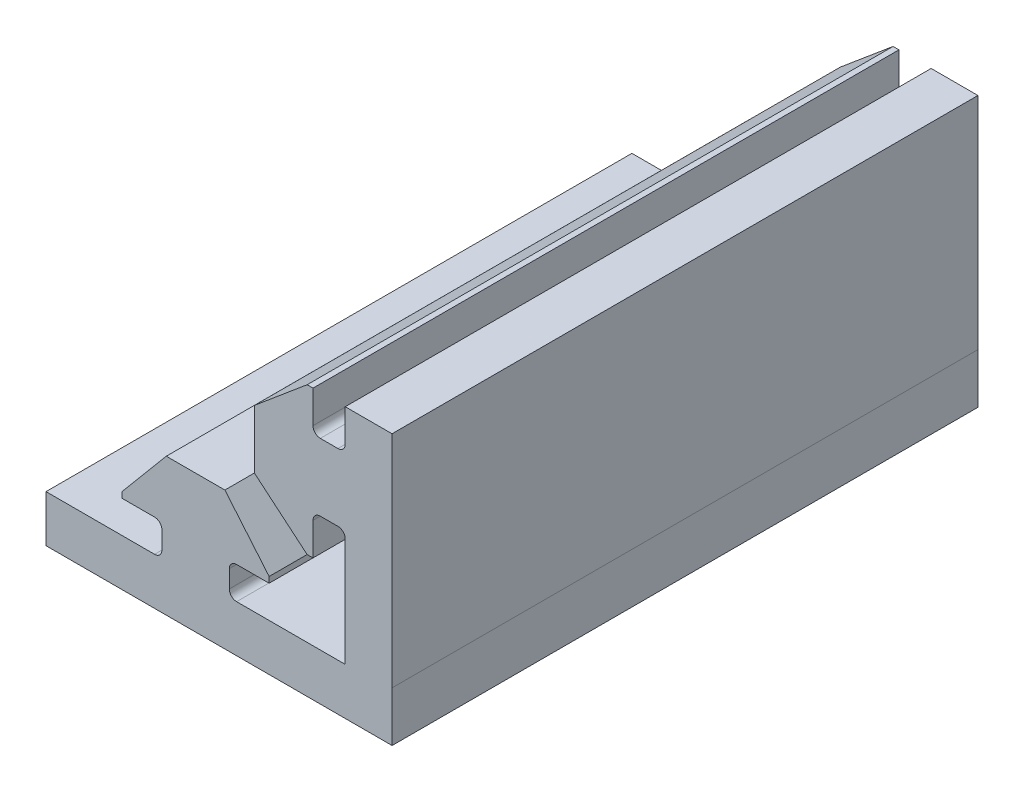
SolidWorks part; units mm, degrees
ref_plane "Front Plane" through (0, 0, 0) normal (0, 0, 1) x (1, 0, 0)
ref_plane "Top Plane" through (0, 0, 0) normal (0, 1, 0) x (1, 0, 0)
ref_plane "Right Plane" through (0, 0, 0) normal (1, 0, 0) x (0, 0, -1)
ref_plane "Plane1" through (0, 0, -3683) normal (0, 0, -1) x (-1, 0, 0)
sketch "Sketch1" plane through (0, 0, -3683) normal (0, 0, -1) x (-1, 0, 0)
  line L0 (7.9453, 3.5889) -> (-1.1987, 3.5889)
  line L1 (-1.8337, 4.2239) -> (-1.8337, 5.7479)
  line L2 (-1.1987, 6.3829) -> (1.6216, 6.3829)
  line L3 (1.6216, 6.3829) -> (1.6216, 6.8909)
  line L4 (1.6216, 6.8909) -> (-2.2147, 11.4629)
  line L5 (-2.2147, 11.4629) -> (-7.2947, 11.4629)
  line L6 (-7.2947, 11.4629) -> (-11.1311, 6.8909)
  line L7 (-11.1311, 6.8909) -> (-11.1311, 6.3829)
  line L8 (-11.1311, 6.3829) -> (-8.3107, 6.3829)
  line L9 (-7.6757, 5.7479) -> (-7.6757, 4.2239)
  line L10 (-8.3107, 3.5889) -> (-17.4547, 3.5889)
  line L11 (-17.7279, 3.8588) -> (-17.7284, 13.0024)
  line L12 (-17.4548, -0.4751) -> (7.9452, -0.4751)
  line L13 (-17.0929, 13.6378) -> (-15.5689, 13.6378)
  line L29 (-17.4547, 3.5889) -> (-17.7279, 3.5889)
  line L30 (-17.4548, -0.4751) -> (-17.7279, -0.4751)
  line L32 (8.2155, 3.5889) -> (8.2155, -0.4751)
  line L34 (8.2155, 3.5889) -> (7.9453, 3.5889)
  line L35 (8.2155, -0.4751) -> (7.9452, -0.4751)
  line L36 (-14.9339, 13.0028) -> (-14.9339, 10.1825)
  line L37 (-14.9339, 10.1825) -> (-14.4259, 10.1825)
  line L38 (-14.4259, 10.1825) -> (-9.8539, 14.0188)
  line L39 (-9.8539, 14.0188) -> (-9.8539, 19.0988)
  line L40 (-9.8539, 19.0988) -> (-14.4259, 22.9352)
  line L41 (-14.4259, 22.9352) -> (-14.9339, 22.9352)
  line L42 (-14.9339, 22.9352) -> (-14.9339, 20.1148)
  line L43 (-15.5689, 19.4798) -> (-17.0929, 19.4798)
  line L44 (-17.7287, 20.1156) -> (-17.7288, 22.9352)
  line L45 (-21.7872, 22.9352) -> (-21.7919, 3.8591)
  line L49 (-17.7288, 22.9352) -> (-21.7872, 22.9352)
  line L51 (-17.7279, 3.5889) -> (-17.7279, 3.8588)
  line L52 (-21.7919, 3.5889) -> (-21.7919, 3.8591)
  line L54 (-17.7279, -0.4751) -> (-21.7919, -0.4751)
  line L56 (-21.7919, -0.4751) -> (-21.7919, 3.5889)
  arc A0 (-1.1987, 3.5889) -> (-1.8337, 4.2239) centre (-1.1987, 4.2239) cw
  arc A1 (-1.8337, 5.7479) -> (-1.1987, 6.3829) centre (-1.1987, 5.7479) cw
  arc A2 (-8.3107, 6.3829) -> (-7.6757, 5.7479) centre (-8.3107, 5.7479) cw
  arc A3 (-7.6757, 4.2239) -> (-8.3107, 3.5889) centre (-8.3107, 4.2239) cw
  arc A4 (-17.7284, 13.0024) -> (-17.0929, 13.6378) centre (-17.0929, 13.0024) cw
  arc A5 (-15.5689, 13.6378) -> (-14.9339, 13.0028) centre (-15.5689, 13.0028) cw
  arc A6 (-14.9339, 20.1148) -> (-15.5689, 19.4798) centre (-15.5689, 20.1148) cw
  arc A7 (-17.0929, 19.4798) -> (-17.7287, 20.1156) centre (-17.0929, 20.1156) cw
  point P44 (-17.699, 22.915)
  point P52 (-21.8512, 22.9184)
  point P55 (0, 0)
  point P56 (0, 0)
  point P57 (0, 0)
extrude "Boss-Extrude1" add sketch "Sketch1" along normal blind 50.8
